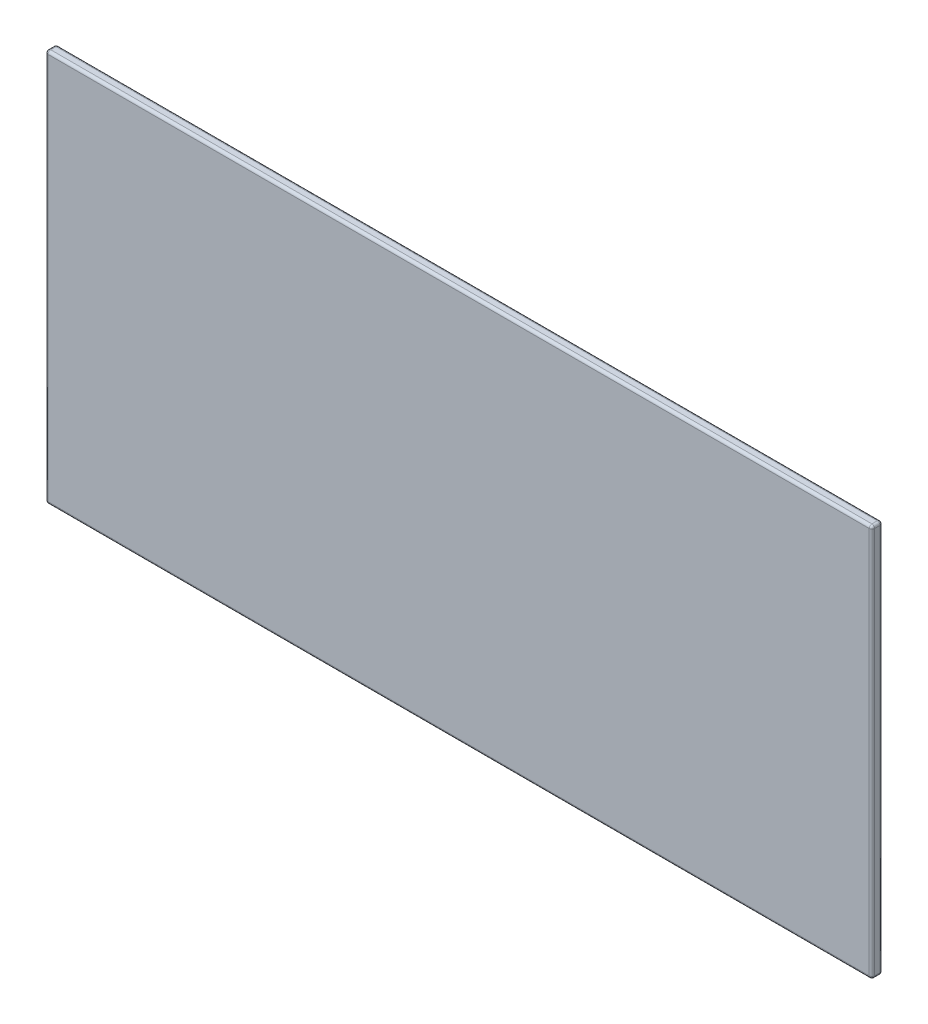
SolidWorks part; units mm, degrees
ref_plane "Front Plane" through (0, 0, 0) normal (0, 0, 1) x (1, 0, 0)
ref_plane "Top Plane" through (0, 0, 0) normal (0, 1, 0) x (1, 0, 0)
ref_plane "Right Plane" through (0, 0, 0) normal (1, 0, 0) x (0, 0, -1)
sketch "Sketch1" plane through (0, 0, 0) normal (0, 0, 1) x (1, 0, 0)
  line L1 (-77.35, -36.75) -> (77.35, -36.75)
  line L2 (-77.35, -36.75) -> (-77.35, 36.75)
  line L3 (-77.35, 36.75) -> (77.35, 36.75)
  line L4 (77.35, -36.75) -> (77.35, 36.75)
  line L5 (-77.35, -36.75) -> (77.35, 36.75) construction
  line L6 (-77.35, 36.75) -> (77.35, -36.75) construction
  point P0 (0, 0)
  dimension "D1" = 154.7
  dimension "D2" = 73.5
extrude "Boss-Extrude1" add sketch "Sketch1" along normal blind 2
fillet "Fillet1" radius 0.5 12 edges at (0, -36.75, 2) (0, -36.75, 0) (-77.35, 0, 2) (-77.35, -36.75, 1) (-77.35, 0, 0) (0, 36.75, 2) (-77.35, 36.75, 1) (0, 36.75, 0) (77.35, -36.75, 1) (77.35, 0, 2) (77.35, 36.75, 1) (77.35, 0, 0)
